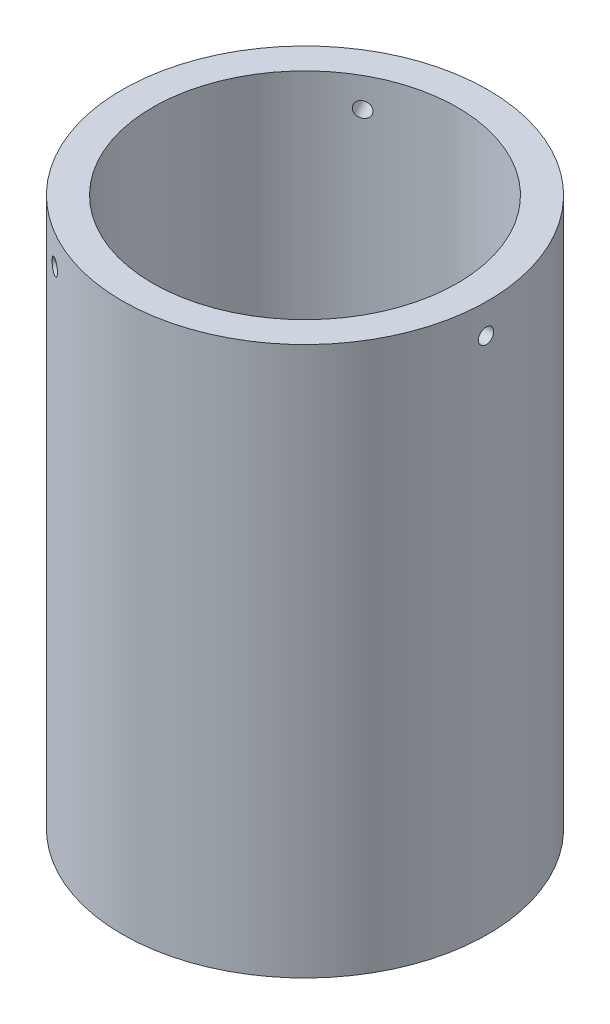
SolidWorks part; units mm, degrees
ref_plane "Front Plane" through (0, 0, 0) normal (0, 0, 1) x (1, 0, 0)
ref_plane "Top Plane" through (0, 0, 0) normal (0, 1, 0) x (1, 0, 0)
ref_plane "Right Plane" through (0, 0, 0) normal (1, 0, 0) x (0, 0, -1)
sketch "Sketch1" plane through (0, 0, 0) normal (0, 1, 0) x (1, 0, 0)
  circle A0 centre (0.5243, 0) radius 19.05
  dimension "D1" = 38.1
extrude "Boss-Extrude1" add sketch "Sketch1" along normal blind 57.15
sketch "Sketch2" plane through (0, 57.15, 0) normal (0, 1, 0) x (1, 0, 0)
  circle A0 centre (0.5243, 0) radius 15.875
  dimension "D1" = 31.75
extrude "Cut-Extrude1" cut sketch "Sketch2" against normal blind 53.975 contours A0
sketch "Sketch3" plane through (0, 0, 0) normal (0, -1, 0) x (-1, 0, 0)
  circle A0 centre (0, 0) radius 6.35
  dimension "D1" = 12.7
extrude "Cut-Extrude2" cut sketch "Sketch3" against normal blind 48.26
ref_plane "Plane1" through (0, 0, -19.05) normal (0, 0, -1) x (-1, 0, 0)
ref_plane "Plane2" through (0, 53.975, 0) normal (0, 1, 0) x (1, 0, 0)
hole_wizard "1/16 (0.0625) Diameter Hole1" positions "3DSketch1" profile "Sketch4" hole size "1/16" standard "ANSI Inch"
sketch3d "3DSketch1"
  point P0 (16.3986, 54.0771, 0.1482)
sketch "Sketch4" plane through (16.3986, 54.0771, 0.1482) normal (0, 1, 0) x (-0.0093, 0, 1)
  line L0 (0, 0) -> (0, 14.636)
  line L1 (0, 14.636) -> (0.7937, 13.97)
  line L2 (0.7937, 13.97) -> (0.7937, 0)
  line L5 (0.7937, 0) -> (0, 0)
  line L10 (0, 14.636) -> (-0.7937, 13.97) construction
  line L11 (0, -6.35) -> (0, 107.95) construction
  dimension "Hole Dia." = 1.5875
  dimension "Hole Depth" = 13.97
  dimension "Drill Angle" = 100
pattern_circular "CirPattern1" count 3 every 120 about axis through (0.5243, 57.15, 0) along (0, -1, 0) of "1/16 (0.0625) Diameter Hole1"
